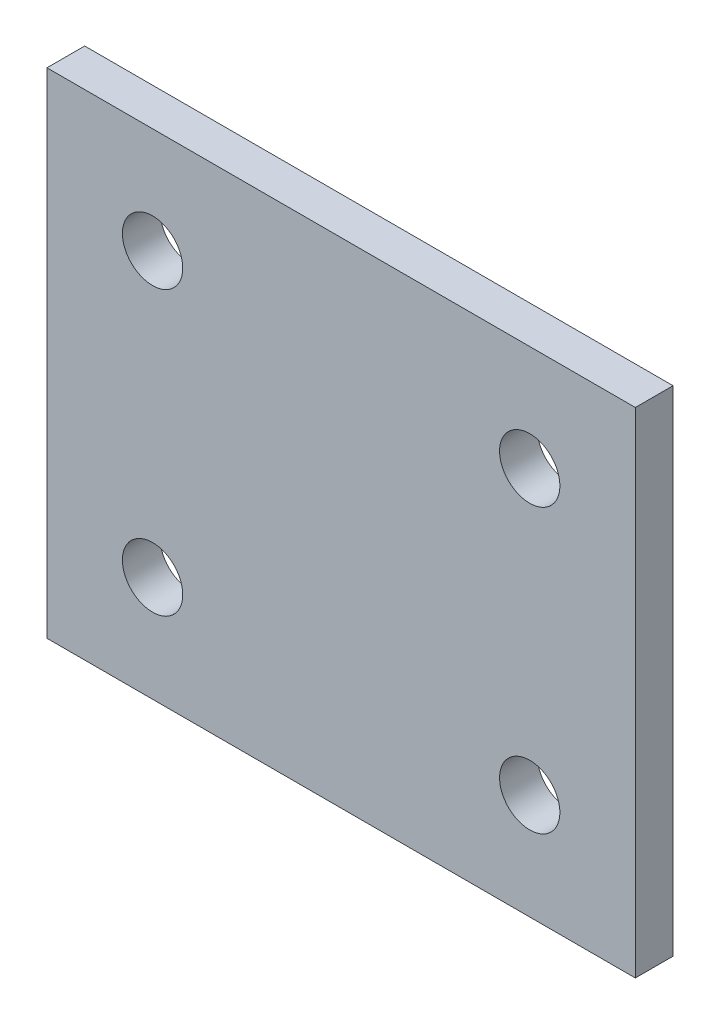
SolidWorks part; units mm, degrees
ref_plane "Front Plane" through (0, 0, 0) normal (0, 0, 1) x (1, 0, 0)
ref_plane "Top Plane" through (0, 0, 0) normal (0, 1, 0) x (1, 0, 0)
ref_plane "Right Plane" through (0, 0, 0) normal (1, 0, 0) x (0, 0, -1)
sketch "Sketch1" plane through (0, 0, 0) normal (0, 0, 1) x (1, 0, 0)
  line L1 (-15.6, -13.1) -> (15.6, -13.1)
  line L2 (-15.6, -13.1) -> (-15.6, 13.1)
  line L3 (-15.6, 13.1) -> (15.6, 13.1)
  line L4 (15.6, -13.1) -> (15.6, 13.1)
  line L5 (-15.6, -13.1) -> (15.6, 13.1) construction
  line L6 (-15.6, 13.1) -> (15.6, -13.1) construction
  circle A0 centre (-10, 7.5) radius 1.6
  circle A1 centre (10, 7.5) radius 1.6
  circle A2 centre (-10, -7.5) radius 1.6
  circle A3 centre (10, -7.5) radius 1.6
  point P0 (0, 0)
  point P14 (0, 0)
  point P15 (0, 0)
  point P16 (0, 0)
  point P17 (0, 0)
  dimension "D7" = 3.2
  dimension "D1" = 31.2
  dimension "D2" = 26.2
  dimension "D3" = 5.6
  dimension "D4" = 5.6
  dimension "D5" = 20
  dimension "D6" = 15
extrude "Boss-Extrude1" add sketch "Sketch1" along normal blind 2
